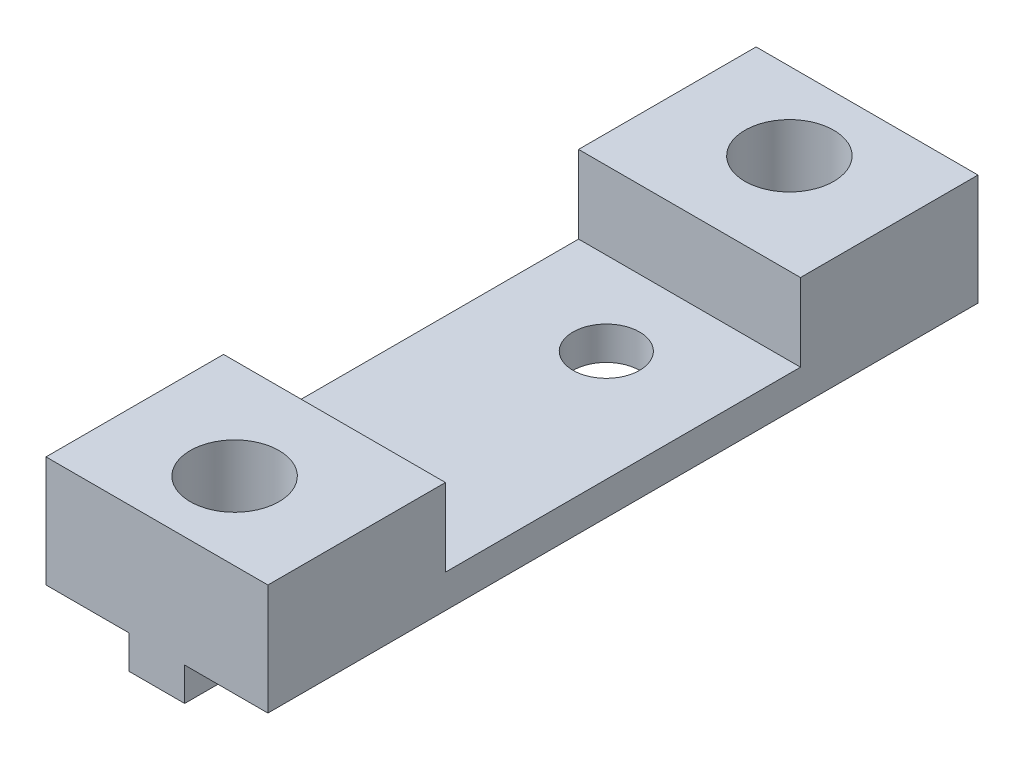
SolidWorks part; units mm, degrees
ref_plane "Front Plane" through (0, 0, 0) normal (0, 0, 1) x (1, 0, 0)
ref_plane "Top Plane" through (0, 0, 0) normal (0, 1, 0) x (1, 0, 0)
ref_plane "Right Plane" through (0, 0, 0) normal (1, 0, 0) x (0, 0, -1)
sketch "Sketch1" plane through (0, 0, 0) normal (0, 1, 0) x (1, 0, 0)
  line L1 (-10, -15) -> (10, -15)
  line L2 (-10, -15) -> (-10, 15)
  line L3 (-10, 15) -> (10, 15)
  line L4 (10, -15) -> (10, 15)
  line L5 (-10, -15) -> (10, 15) construction
  line L6 (-10, 15) -> (10, -15) construction
  point P0 (0, 0)
  dimension "D1" = 20
  dimension "D2" = 30
extrude "Boss-Extrude1" add sketch "Sketch1" along normal blind 3
sketch "Sketch2" plane through (0, 0, 0) normal (0, -1, 0) x (1, 0, 0)
  line L0 (10, -15) -> (-10, -15) construction
  line L1 (-2.5, -15) -> (2.5, -15)
  line L2 (-2.5, -15) -> (-2.5, -3)
  line L3 (-2.5, -3) -> (2.5, -3)
  line L4 (2.5, -15) -> (2.5, -3)
  line L5 (-2.5, -15) -> (2.5, -3) construction
  line L6 (-2.5, -3) -> (2.5, -15) construction
  point P0 (0, -9)
  dimension "D1" = 0
  dimension "D2" = 5
  dimension "D3" = 0
  dimension "D4" = 12
extrude "Boss-Extrude2" add sketch "Sketch2" along normal blind 3
sketch "Sketch3" plane through (0, 3, 0) normal (0, 1, 0) x (1, 0, 0)
  line L0 (10, 15) -> (-10, 15) construction
  circle A0 centre (0, 8) radius 4
  circle A1 centre (0, 8) radius 7
  dimension "D1" = 14
  dimension "D2" = 7
  dimension "D3" = 8
extrude "Boss-Extrude3" add sketch "Sketch3" along normal blind 7
sketch "Sketch4" plane through (0, 3, 0) normal (0, 1, 0) x (1, 0, 0)
  circle A1 centre (0, 8) radius 4
  circle A2 centre (0, 8) radius 4
  dimension "D1" = 0
extrude "Boss-Extrude4" add sketch "Sketch4" along normal blind 1
sketch "Sketch5" plane through (0, 3, 0) normal (0, 1, 0) x (1, 0, 0)
  line L0 (-10, -15) -> (10, -15) construction
  circle A0 centre (0, -8.5) radius 3
  point P4 (0, 0)
  point P7 (-0.7919, -3)
  dimension "D1" = 6
  dimension "D2" = 6.5
  dimension "D3" = 0
extrude "Cut-Extrude1" cut sketch "Sketch5" against normal through all both and the other way through all
chamfer "Chamfer1" [suppressed] distance 4 angle 45
sketch "Sketch6" plane through (0, 3, 0) normal (0, 1, 0) x (1, 0, 0)
  line L0 (10, -15) -> (10, 15) construction
  line L1 (-10, 15) -> (10, 15)
  line L2 (-10, 15) -> (-10, -1)
  line L3 (-10, -1) -> (10, -1)
  line L4 (10, 15) -> (10, -1)
  circle A0 centre (0, 8) radius 7 construction
  circle A1 centre (0, 8) radius 7
  circle A3 centre (0, 8) radius 4
  circle A4 centre (0, 8) radius 4
  line M6 (10, 15) -> (0, 15)
  circle M7 centre (0, 8) radius 7
  line M8 (0, 15) -> (-10, 15)
  line M9 (-10, 15) -> (-10, -15)
  line M11 (10, -15) -> (10, 15)
  dimension "D1" = 16
  dimension "D2" = 0
extrude "Boss-Extrude6" add sketch "Sketch6" along normal up to surface (7 mm away) contours A4 M7 | L3 M9 M11 M6 M7 M8 up to face at (0, 10, -1)
ref_plane "Plane1" through (0, 0, -8) normal (0, 0, 1) x (1, 0, 0)
ref_plane "Plane2" through (0, 0, 17) normal (0, 0, 1) x (1, 0, 0)
sketch "Sketch7" plane through (0, 0, 15) normal (0, 0, 1) x (1, 0, 0)
  line L4 (-10, 0) -> (10, 0)
  line L5 (10, 0) -> (10, 3)
  line L6 (10, 3) -> (-10, 3)
  line L7 (-10, 3) -> (-10, 0)
  line L8 (-10, 0) -> (10, 0)
  line L9 (10, 0) -> (10, 3)
  line L10 (10, 3) -> (-10, 3)
  line L11 (-10, 3) -> (-10, 0)
  dimension "D1" = 0
extrude "Boss-Extrude7" add sketch "Sketch7" along normal blind 19
mirror "Mirror3" about plane through (0, 0, 17) normal (0, 0, 1) of "Boss-Extrude6", "Boss-Extrude4", "Boss-Extrude3", "Boss-Extrude2", "Boss-Extrude1"
sketch "Sketch8" plane through (0, 0, 37) normal (0, 0, -1) x (-1, 0, 0)
  line L4 (2.5, 0) -> (-2.5, 0)
  line L5 (-2.5, 0) -> (-2.5, -3)
  line L6 (-2.5, -3) -> (2.5, -3)
  line L7 (2.5, -3) -> (2.5, 0)
  line L8 (2.5, 0) -> (-2.5, 0)
  line L9 (-2.5, 0) -> (-2.5, -3)
  line L10 (-2.5, -3) -> (2.5, -3)
  line L11 (2.5, -3) -> (2.5, 0)
  dimension "D1" = 0
extrude "Boss-Extrude8" add sketch "Sketch8" along normal blind 12
